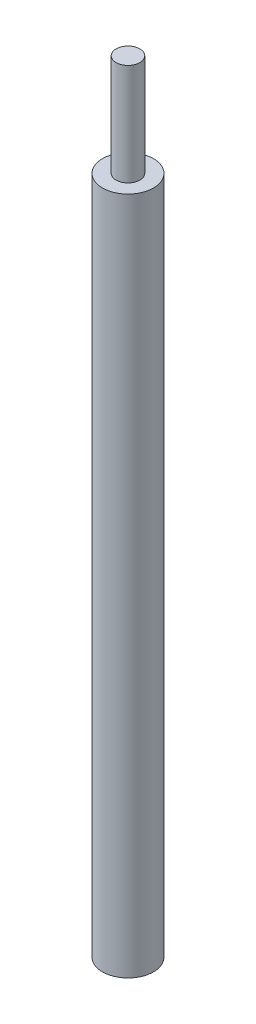
SolidWorks part; units mm, degrees
ref_plane "Front Plane" through (0, 0, 0) normal (0, 0, 1) x (1, 0, 0)
ref_plane "Top Plane" through (0, 0, 0) normal (0, 1, 0) x (1, 0, 0)
ref_plane "Right Plane" through (0, 0, 0) normal (1, 0, 0) x (0, 0, -1)
sketch "Sketch1" plane through (0, 0, 0) normal (0, 1, 0) x (1, 0, 0)
  circle A0 centre (0, 0) radius 1.5
  dimension "D1" = 3
extrude "Boss-Extrude1" add sketch "Sketch1" along normal blind 40
sketch "Sketch2" plane through (0, 40, 0) normal (0, 1, 0) x (1, 0, 0)
  circle A0 centre (0, 0) radius 0.7
  dimension "D1" = 1.4
extrude "Boss-Extrude2" add sketch "Sketch2" along normal blind 6
